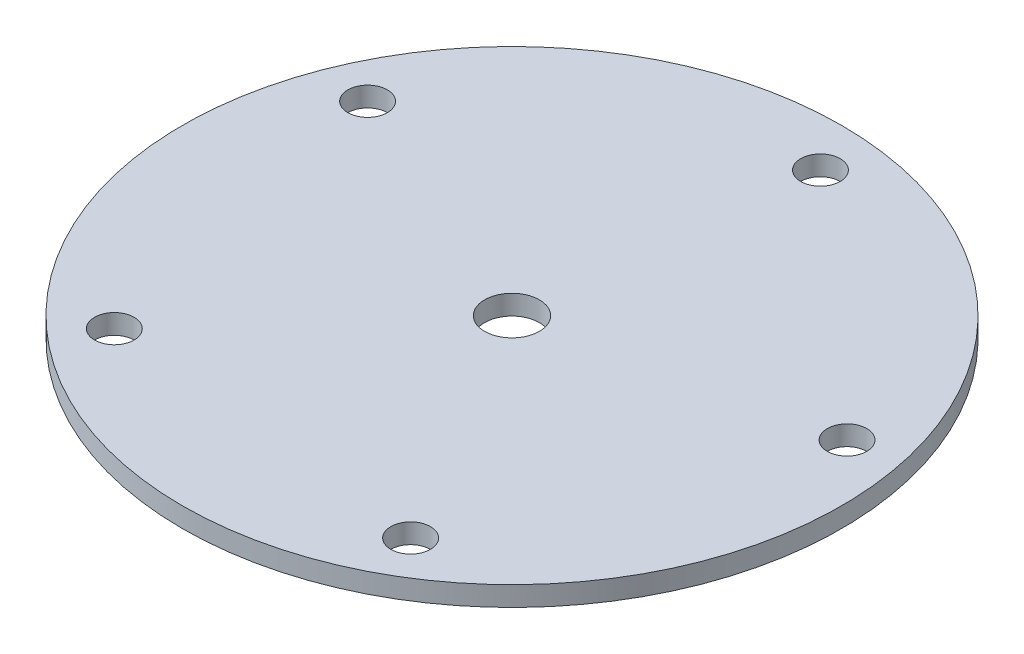
SolidWorks part; units mm, degrees
ref_plane "Front Plane" through (0, 0, 0) normal (0, 0, 1) x (1, 0, 0)
ref_plane "Top Plane" through (0, 0, 0) normal (0, 1, 0) x (1, 0, 0)
ref_plane "Right Plane" through (0, 0, 0) normal (1, 0, 0) x (0, 0, -1)
sketch "Sketch1" plane through (0, 0, 0) normal (0, 1, 0) x (1, 0, 0)
  circle A0 centre (0, 0) radius 50
extrude "Boss-Extrude1" add sketch "Sketch1" along normal blind 3
sketch "Sketch2" plane through (0, 3, 0) normal (0, 1, 0) x (1, 0, 0)
  circle A0 centre (0, 0) radius 4.15
extrude "Cut-Extrude1" cut sketch "Sketch2" against normal blind 5
sketch "Sketch3" plane through (0, 3, 0) normal (0, 1, 0) x (1, 0, 0)
  circle A0 centre (-28.4516, -31.8833) radius 3
  circle A1 centre (-39.1148, 17.2066) radius 3
  circle A2 centre (4.2773, 42.5176) radius 3
  circle A3 centre (41.7584, 9.0707) radius 3
  circle A4 centre (21.5308, -36.9116) radius 3
  point P12 (0, 0)
  dimension "D1" = 5
extrude "Cut-Extrude2" cut sketch "Sketch3" against normal blind 10
